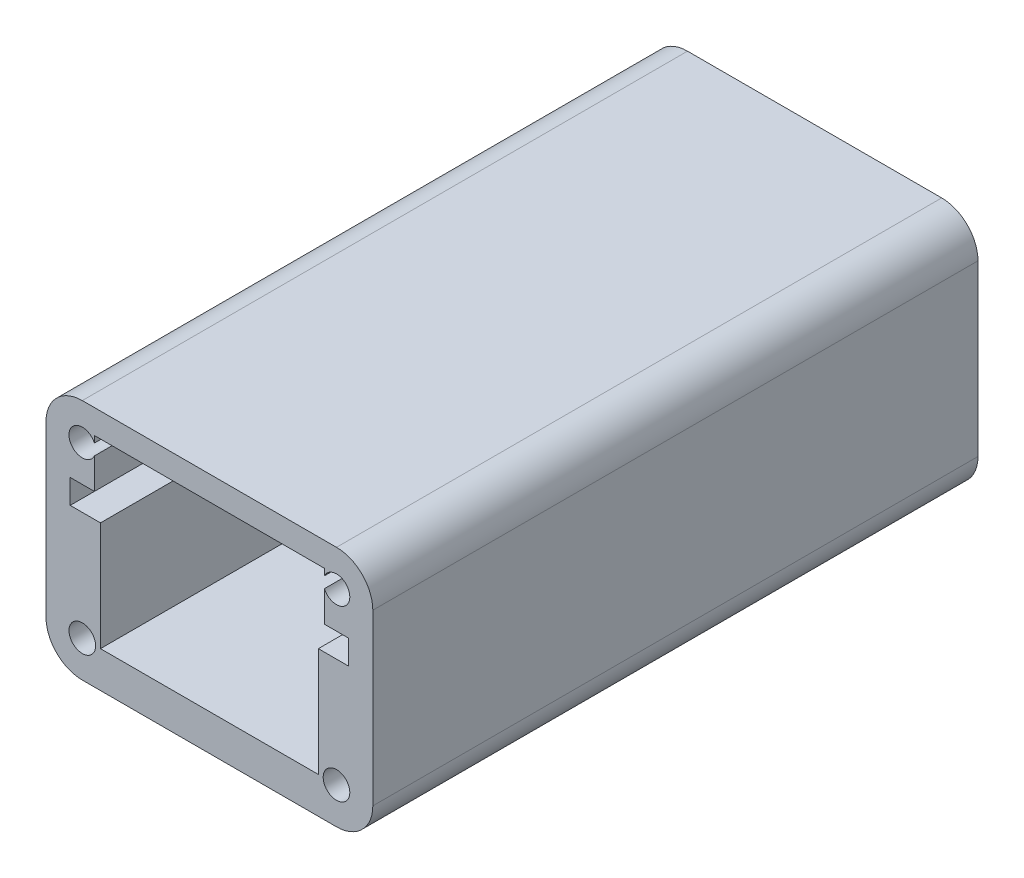
SolidWorks part; units mm, degrees
ref_plane "Front Plane" through (0, 0, 0) normal (0, 0, 1) x (1, 0, 0)
ref_plane "Top Plane" through (0, 0, 0) normal (0, 1, 0) x (1, 0, 0)
ref_plane "Right Plane" through (0, 0, 0) normal (1, 0, 0) x (0, 0, -1)
sketch "Sketch1" plane through (0, 0, 0) normal (0, 0, 1) x (1, 0, 0)
  line L0 (0, 20) -> (0, 0)
  line L1 (0, 0) -> (27, 0)
  line L3 (0, 20) -> (27, 20)
  line L5 (27, 20) -> (27, 0)
  line L6 (4, 17) -> (23, 17)
  line L8 (4, 3) -> (23, 3)
  line L10 (4, 16) -> (4, 4)
  line L12 (23, 16) -> (23, 4)
  line L14 (4, 16) -> (4, 17)
  line L15 (4, 4) -> (4, 3)
  line L16 (23, 16) -> (23, 17)
  line L17 (23, 4) -> (23, 3)
  line L19 (4, 16) -> (23, 16) construction
  line L20 (4, 4) -> (23, 4) construction
  line L21 (3, 17) -> (3, 3) construction
  line L22 (3, 17) -> (24, 17) construction
  line L23 (3, 3) -> (24, 3) construction
  line L24 (24, 17) -> (24, 3) construction
  dimension "D1" = 20
  dimension "D2" = 27
  dimension "D3" = 3
  dimension "D4" = 4
extrude "Boss-Extrude1" add sketch "Sketch1" against normal blind 50
sketch "Sketch2" plane through (0, 0, -50) normal (0, 0, -1) x (-1, 0, 0)
  line L1 (-23, 17) -> (-4, 17)
  line L2 (-23, 17) -> (-23, 3)
  line L3 (-23, 3) -> (-4, 3)
  line L4 (-4, 17) -> (-4, 3)
extrude "Boss-Extrude2" add sketch "Sketch2" against normal blind 2
sketch "Sketch3" plane through (0, 0, 0) normal (0, 0, 1) x (1, 0, 0)
  line L0 (13.5, 14) -> (13.5, 12) construction
  line L1 (2, 14) -> (25, 14)
  line L2 (2, 14) -> (2, 12)
  line L3 (2, 12) -> (25, 12)
  line L4 (25, 14) -> (25, 12)
  line L5 (13.5, 20) -> (13.5, 18.1622) construction
  line L6 (27, 20) -> (0, 20) construction
  line L7 (27, 0) -> (27, 20) construction
  dimension "D1" = 6
  dimension "D2" = 2
  dimension "D3" = 2
extrude "Cut-Extrude1" cut sketch "Sketch3" against normal up to surface (48 mm away) up to face at (13.5, 10, -48)
sketch "Sketch4" plane through (0, 0, 0) normal (0, 0, 1) x (1, 0, 0)
  line L0 (4, 3) -> (23, 3) construction
  line L1 (4, 12) -> (4.5, 12)
  line L2 (4, 12) -> (4, 3)
  line L3 (4, 3) -> (4.5, 3)
  line L4 (4.5, 12) -> (4.5, 3)
  line L5 (23, 14) -> (23, 17) construction
  line L6 (23, 12) -> (22.5, 12)
  line L7 (23, 12) -> (23, 3)
  line L8 (23, 3) -> (22.5, 3)
  line L9 (22.5, 12) -> (22.5, 3)
  line L10 (4, 17) -> (23, 17)
  line L11 (4, 17) -> (4, 16.5)
  line L12 (4, 16.5) -> (23, 16.5)
  line L13 (23, 17) -> (23, 16.5)
  dimension "D1" = 0.5
  dimension "D2" = 0.5
  dimension "D3" = 0.5
extrude "Boss-Extrude3" add sketch "Sketch4" against normal up to surface (48 mm away) up to face at (13.5, 12, -48)
fillet "Fillet1" radius 3 4 edges at (27, 0, -25) (27, 20, -25) (0, 0, -25) (0, 20, -25)
sketch "Sketch6" plane through (0, 0, 0) normal (0, 0, 1) x (1, 0, 0)
  circle A0 centre (3, 17) radius 1.1
  circle A1 centre (24, 17) radius 1.1
  circle A2 centre (24, 3) radius 1.1
  circle A3 centre (3, 3) radius 1.1
  dimension "D1" = 2.2
extrude "Cut-Extrude2" cut sketch "Sketch6" against normal blind 6
ref_plane "Plane1" through (0, 0, -25) normal (0, 0, 1) x (1, 0, 0)
sketch "Sketch10" plane through (0, 0, -25) normal (0, 0, 1) x (1, 0, 0)
  line L0 (27, 10) -> (42, 10) construction
  line L1 (27, 3) -> (27, 17) construction
  dimension "D1" = 15
sketch "Sketch11" plane through (0, 0, -25) normal (0, 0, 1) x (1, 0, 0)
  line L0 (42, 10) -> (42, 50) construction
  line L1 (27, 10) -> (42, 10)
  line L2 (42, 10) -> (42, 50)
  dimension "D1" = 40
ref_plane "Plane3" through (0, 50, 0) normal (0, 1, 0) x (1, 0, 0)
sketch "Sketch12" plane through (0, 50, 0) normal (0, 1, 0) x (1, 0, 0)
  line L0 (42, 17.5) -> (42, 32.5) construction
  line L3 (39.5, 17.5) -> (39.5, 32.5)
  line L4 (44.5, 17.5) -> (44.5, 32.5)
  arc A0 (39.5, 17.5) -> (44.5, 17.5) centre (42, 17.5) ccw
  arc A1 (44.5, 32.5) -> (39.5, 32.5) centre (42, 32.5) ccw
  point P6 (42, 25)
  dimension "D1" = 5
  dimension "D2" = 15
sweep "Sweep1" [suppressed] add profiles "Sketch12" path "Sketch11"
ref_plane "Plane4" through (13.5, 0, 0) normal (1, 0, 0) x (0, 0, -1)
mirror "Mirror1" [suppressed] about plane through (13.5, 0, 0) normal (1, 0, 0)
sketch "Sketch13" [suppressed] plane through (44.5, 0, 0) normal (1, 0, 0) x (0, 0, -1)
  circle A0 centre (25, 42.0867) radius 3.2577
sketch "Sketch14" plane through (0, 0, 0) normal (0, 0, 1) x (1, 0, 0)
  line L1 (4, 16.5) -> (23, 16.5)
  line L2 (4, 16.5) -> (4, 18)
  line L3 (4, 18) -> (23, 18)
  line L4 (23, 16.5) -> (23, 18)
  dimension "D1" = 1.5
extrude "Cut-Extrude3" cut sketch "Sketch14" against normal up to surface (48 mm away) and the other way through all up to face at (13.5, 11.9167, -48)
